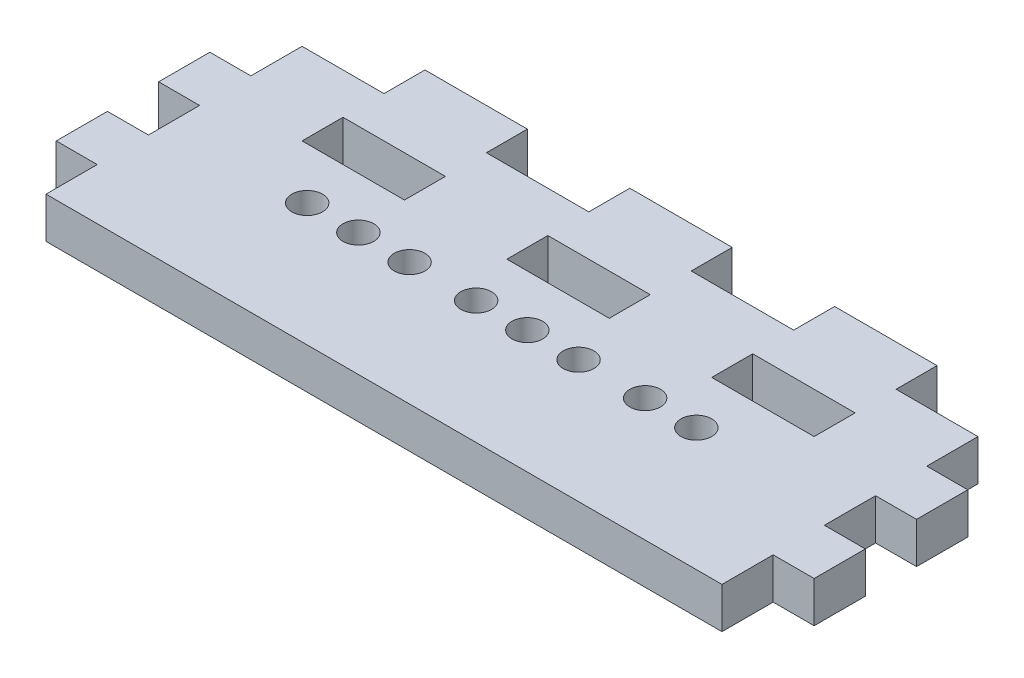
SolidWorks part; units mm, degrees
material "Maple"
ref_plane "Front Plane" through (0, 0, 0) normal (0, 0, 1) x (1, 0, 0)
ref_plane "Top Plane" through (0, 0, 0) normal (0, 1, 0) x (1, 0, 0)
ref_plane "Right Plane" through (0, 0, 0) normal (1, 0, 0) x (0, 0, -1)
sketch "Sketch1" plane through (0, 0, 0) normal (0, 1, 0) x (1, 0, 0)
  line L1 (0, 0) -> (66, 0)
  line L2 (0, 0) -> (0, -25)
  line L3 (0, -25) -> (66, -25)
  line L4 (66, 0) -> (66, -25)
  dimension "D1" = 66
  dimension "D2" = 25
extrude "Boss-Extrude1" add sketch "Sketch1" along normal blind 4
sketch "Sketch2" plane through (0, 4, 0) normal (0, 1, 0) x (1, 0, 0)
  line L9 (66, -25) -> (66, 0) construction
  line L10 (0, 0) -> (0, -25) construction
  line L11 (0, -15) -> (-4, -15)
  line L12 (0, -15) -> (0, -20)
  line L13 (0, -20) -> (-4, -20)
  line L14 (-4, -15) -> (-4, -20)
  line L15 (66, -15) -> (70, -15)
  line L16 (66, -15) -> (66, -20)
  line L17 (66, -20) -> (70, -20)
  line L18 (70, -15) -> (70, -20)
  line L19 (0, -25) -> (66, -25) construction
  dimension "D1" = 4
  dimension "D2" = 5
  dimension "D3" = 5
extrude "Boss-Extrude2" add sketch "Sketch2" against normal through all
pattern_linear "LPattern1" count 2 spacing 10 along (0, 0, -1) of "Boss-Extrude2"
sketch "Sketch3" plane through (0, 4, 0) normal (0, 1, 0) x (1, 0, 0)
  line L0 (33, -25) -> (33, 0) construction
  line L1 (0, -25) -> (66, -25) construction
  line L2 (66, 0) -> (0, 0) construction
  line L4 (28, 0) -> (38, 0)
  line L5 (28, 0) -> (28, 4)
  line L6 (28, 4) -> (38, 4)
  line L7 (38, 0) -> (38, 4)
  line L8 (28, 0) -> (38, 4) construction
  line L9 (28, 4) -> (38, 0) construction
  point P6 (33, 2)
  dimension "D1" = 4
  dimension "D2" = 10
extrude "Boss-Extrude3" add sketch "Sketch3" against normal through all
pattern_linear "LPattern2" count 2 spacing 20 along (1, 0, 0) count 2 spacing 20 along (-1, 0, 0) of "Boss-Extrude3"
sketch "Sketch4" plane through (0, 0, 0) normal (0, -1, 0) x (1, 0, 0)
  line L0 (33, -4) -> (33, 25) construction
  line L1 (8, 4) -> (18, 4)
  line L2 (8, 4) -> (8, 8)
  line L3 (8, 8) -> (18, 8)
  line L4 (18, 4) -> (18, 8)
  line L5 (28, 4) -> (38, 4)
  line L6 (28, 4) -> (28, 8)
  line L7 (28, 8) -> (38, 8)
  line L8 (38, 4) -> (38, 8)
  line L9 (48, 4) -> (58, 4)
  line L10 (48, 4) -> (48, 8)
  line L11 (48, 8) -> (58, 8)
  line L12 (58, 4) -> (58, 8)
  line L13 (38, -4) -> (28, -4) construction
  line L14 (0, 25) -> (66, 25) construction
  dimension "D2" = 10
  dimension "D3" = 5
  dimension "D4" = 4
  dimension "D5" = 10
  dimension "D6" = 10
  dimension "D7" = 10
  dimension "D8" = 10
  dimension "D1" = 17
extrude "Cut-Extrude1" cut sketch "Sketch4" against normal through all
sketch "Sketch7" plane through (0, 0, 0) normal (0, -1, 0) x (1, 0, 0)
  line L0 (66, 13) -> (0, 13) construction
  line L1 (66, 15) -> (66, 10) construction
  line L2 (0, 10) -> (0, 15) construction
  line L3 (18, 8) -> (8, 8) construction
  circle A0 centre (54.5, 13) radius 1.5
  circle A1 centre (49.5, 13) radius 1.5
  circle A2 centre (44.5, 13) radius 1.5
  circle A3 centre (38, 13) radius 1.5
  circle A4 centre (33, 13) radius 1.5
  circle A5 centre (11.5, 13) radius 1.5
  circle A6 centre (16.5, 13) radius 1.5
  circle A7 centre (21.5, 13) radius 1.5
  circle A8 centre (28, 13) radius 1.5
  dimension "D2" = 3
  dimension "D1" = 5
  dimension "D3" = 5
  dimension "D4" = 5
  dimension "D5" = 5
  dimension "D6" = 5
  dimension "D7" = 5
  dimension "D8" = 5
  dimension "D9" = 11.5
  dimension "D10" = 11.5
  dimension "D11" = 33
extrude "Cut-Extrude3" [suppressed] cut sketch "Sketch7" against normal through all
sketch "Sketch8" plane through (0, 4, 0) normal (0, 1, 0) x (1, 0, 0)
  line L0 (66, -13) -> (0, -13) construction
  line L1 (66, -15) -> (66, -10) construction
  line L2 (0, -10) -> (0, -15) construction
  line L3 (58, -8) -> (48, -8) construction
  circle A0 centre (51.5, -13) radius 1.5
  circle A1 centre (46.5, -13) radius 1.5
  circle A2 centre (40, -13) radius 1.5
  circle A3 centre (35, -13) radius 1.5
  circle A4 centre (30, -13) radius 1.5
  circle A5 centre (23.5, -13) radius 1.5
  circle A6 centre (18.5, -13) radius 1.5
  circle A7 centre (13.5, -13) radius 1.5
  dimension "D2" = 3
  dimension "D1" = 5
  dimension "D3" = 5
  dimension "D4" = 5
  dimension "D5" = 5
  dimension "D6" = 5
  dimension "D7" = 5
  dimension "D8" = 14.5
  dimension "D9" = 26
  dimension "D10" = 13.5
extrude "Cut-Extrude4" cut sketch "Sketch8" against normal through all
equation "\"D6@Sketch4\"=\"D5@Sketch4\""
equation "\"D7@Sketch4\"=\"D2@Sketch4\""
equation "\"D8@Sketch4\"=\"D2@Sketch4\""
equation "\"D4@Sketch7\"=\"D3@Sketch7\""
equation "\"D5@Sketch7\"=\"D3@Sketch7\""
equation "\"D6@Sketch7\"=\"D3@Sketch7\""
equation "\"D7@Sketch7\"=\"D3@Sketch7\""
equation "\"D8@Sketch7\"=\"D3@Sketch7\""
equation "\"D4@Sketch8\"=\"D3@Sketch8\""
equation "\"D5@Sketch8\"=\"D3@Sketch8\""
equation "\"D6@Sketch8\"=\"D3@Sketch8\""
equation "\"D7@Sketch8\"=\"D3@Sketch8\""
